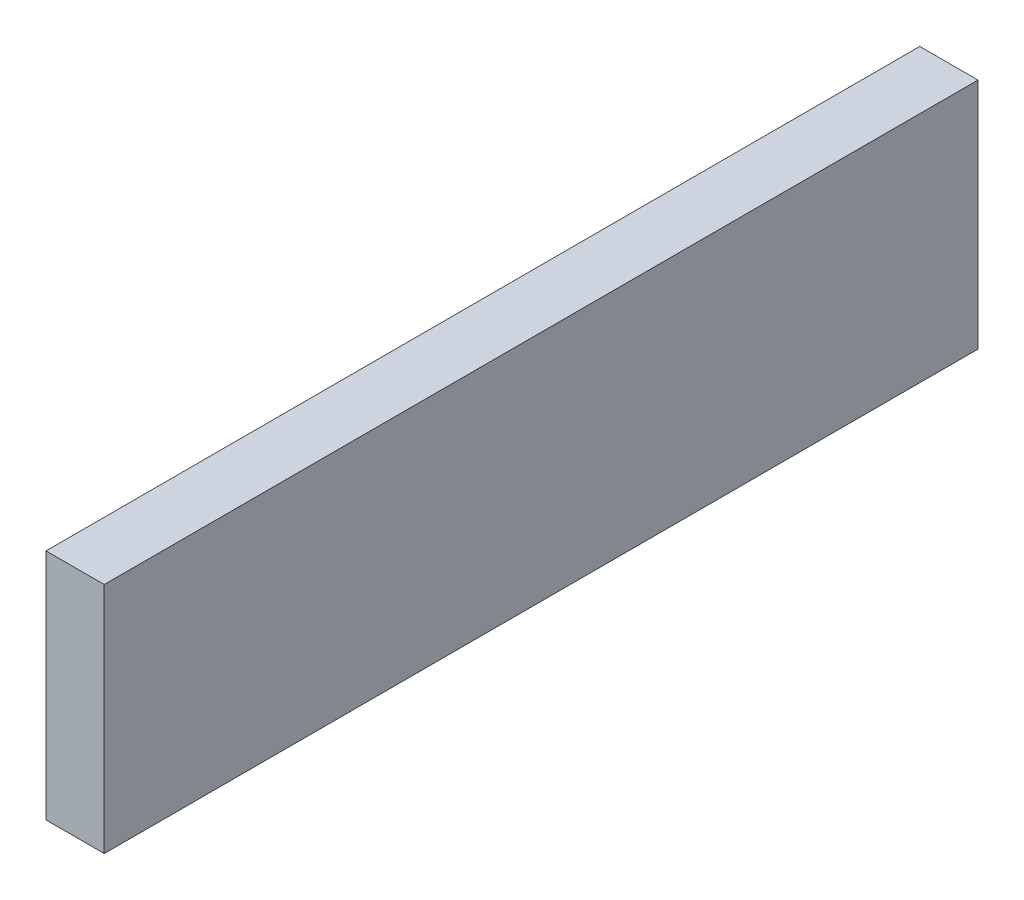
SolidWorks part; units mm, degrees
ref_plane "Front Plane" through (0, 0, 0) normal (0, 0, 1) x (1, 0, 0)
ref_plane "Top Plane" through (0, 0, 0) normal (0, 1, 0) x (1, 0, 0)
ref_plane "Right Plane" through (0, 0, 0) normal (1, 0, 0) x (0, 0, -1)
sketch "Sketch1" plane through (0, 0, 0) normal (1, 0, 0) x (0, 0, -1)
  line L1 (0, 0) -> (95.25, 0)
  line L2 (0, 0) -> (0, -25.4)
  line L3 (0, -25.4) -> (95.25, -25.4)
  line L4 (95.25, 0) -> (95.25, -25.4)
  dimension "D1" = 95.25
  dimension "D2" = 25.4
extrude "Boss-Extrude1" add sketch "Sketch1" along normal blind 6.35
